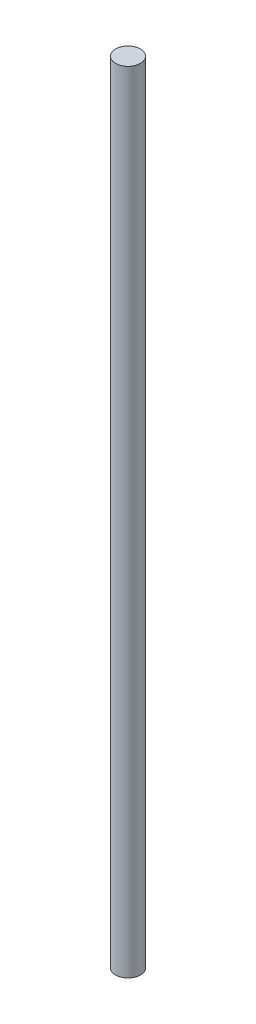
SolidWorks part; units mm, degrees
ref_plane "Front Plane" through (0, 0, 0) normal (0, 0, 1) x (1, 0, 0)
ref_plane "Top Plane" through (0, 0, 0) normal (0, 1, 0) x (1, 0, 0)
ref_plane "Right Plane" through (0, 0, 0) normal (1, 0, 0) x (0, 0, -1)
sketch "Sketch1" plane through (0, 0, 0) normal (0, 1, 0) x (1, 0, 0)
  circle A0 centre (0, 0) radius 0.6
  dimension "D1" = 1.2
extrude "Boss-Extrude1" add sketch "Sketch1" along normal blind 38
